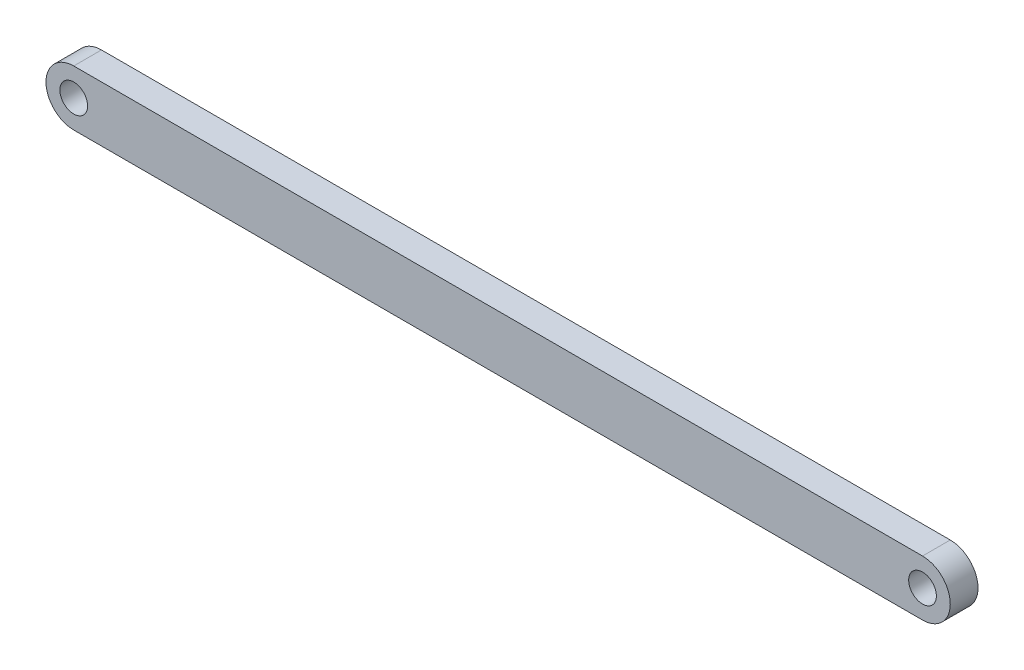
SolidWorks part; units mm, degrees
ref_plane "前视基准面" through (0, 0, 0) normal (0, 0, 1) x (1, 0, 0)
ref_plane "上视基准面" through (0, 0, 0) normal (0, 1, 0) x (1, 0, 0)
ref_plane "右视基准面" through (0, 0, 0) normal (1, 0, 0) x (0, 0, -1)
sketch "草图1" plane through (0, 0, 0) normal (0, 0, 1) x (1, 0, 0)
  line L0 (0, 0) -> (306, 0) construction
  line L1 (0, 10) -> (306, 10)
  line L2 (0, -10) -> (306, -10)
  arc A0 (0, 10) -> (0, -10) centre (0, 0) ccw
  arc A1 (306, -10) -> (306, 10) centre (306, 0) ccw
  circle A2 centre (0, 0) radius 5
  circle A3 centre (306, 0) radius 5
  point P3 (153, 0)
  dimension "D1" = 10
  dimension "D2" = 10
  dimension "D3" = 306
extrude "凸台-拉伸1" add sketch "草图1" along normal blind 10
